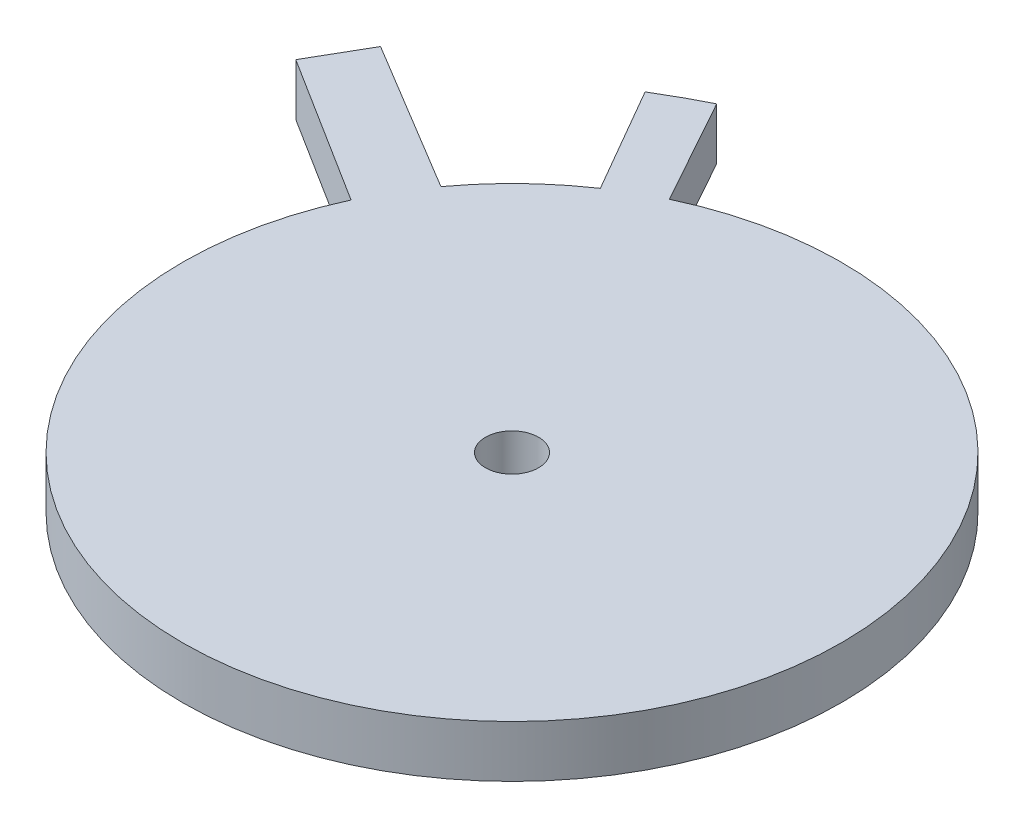
SolidWorks part; units mm, degrees
ref_plane "Front" through (0, 0, 0) normal (0, 0, 1) x (1, 0, 0)
ref_plane "Top" through (0, 0, 0) normal (0, 1, 0) x (1, 0, 0)
ref_plane "Right" through (0, 0, 0) normal (1, 0, 0) x (0, 0, -1)
sketch "草图1" plane through (0, 0, 0) normal (0, 1, 0) x (1, 0, 0)
  line L0 (0, 0) -> (24.7104, 0) construction
  line L1 (0, 0) -> (23.0546, 13.3106) construction
  line L2 (0, 0) -> (12.4412, 21.5488) construction
  line L3 (0, 0) -> (0, 26.6143) construction
  line L4 (0.8361, 0.4611) -> (-18.2967, 33.6001) construction
  line L5 (0.8242, 0.4383) -> (-33.6792, 20.3589) construction
  line L6 (-83.7727, 49.2804) -> (-86.3992, 44.7313)
  line L7 (-86.3992, 44.7313) -> (-57.6454, 26.6318)
  line L8 (-83.7727, 49.2804) -> (-80.4201, 55.0874)
  line L9 (-80.4201, 55.0874) -> (-51.2247, 37.5271)
  line L10 (-42.6243, 75.7367) -> (-47.3596, 73.0027)
  line L11 (-47.3596, 73.0027) -> (-35.5783, 52.5969)
  line L12 (-42.6243, 75.7367) -> (-38.4636, 77.9037)
  line L13 (-38.4636, 77.9037) -> (-27.095, 57.4292)
  arc A0 (-35.5783, 52.5969) -> (-51.2247, 37.5271) centre (0, 0) ccw
  arc A1 (-57.6454, 26.6318) -> (-27.095, 57.4292) centre (0, 0) ccw
  circle A2 centre (0, 0) radius 5.1143
  dimension "D1" = 127
  dimension "D2" = 30
  dimension "D3" = 30
  dimension "D4" = 30
  dimension "D5" = 30
  dimension "D6" = 30
  dimension "D7" = 30
extrude "凸台-拉伸1" add sketch "草图1" along normal blind 10
